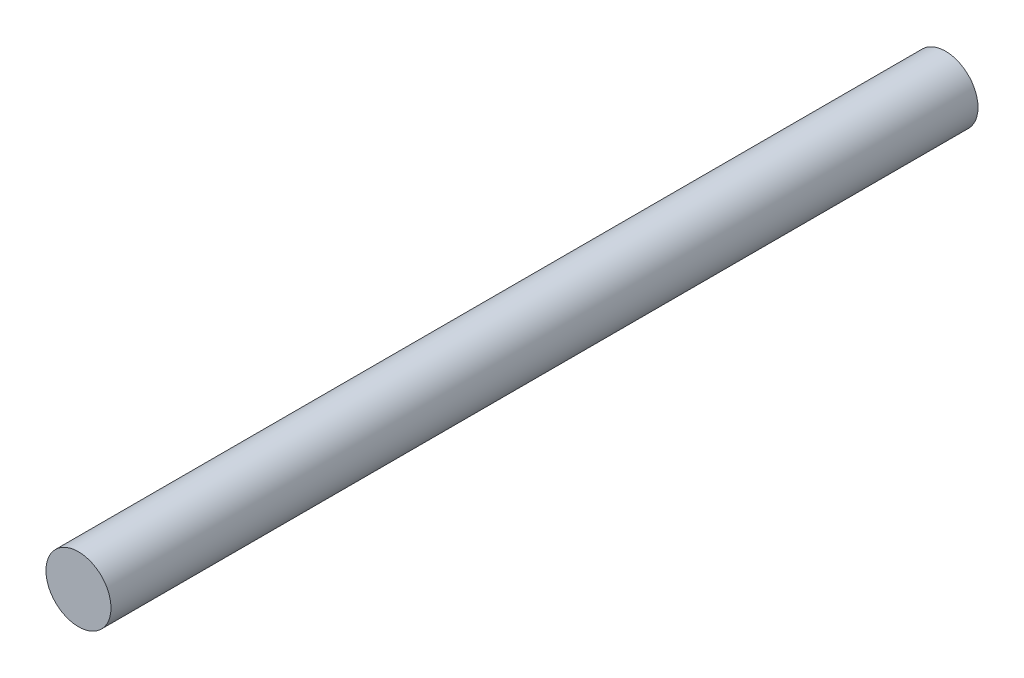
SolidWorks part; units mm, degrees
ref_plane "Front Plane" through (0, 0, 0) normal (0, 0, 1) x (1, 0, 0)
ref_plane "Top Plane" through (0, 0, 0) normal (0, 1, 0) x (1, 0, 0)
ref_plane "Right Plane" through (0, 0, 0) normal (1, 0, 0) x (0, 0, -1)
sketch "草圖1" plane through (0, 0, 0) normal (0, 0, 1) x (1, 0, 0)
  circle A0 centre (0, 0) radius 3
extrude "填料-伸長1" add sketch "草圖1" along normal blind 80
